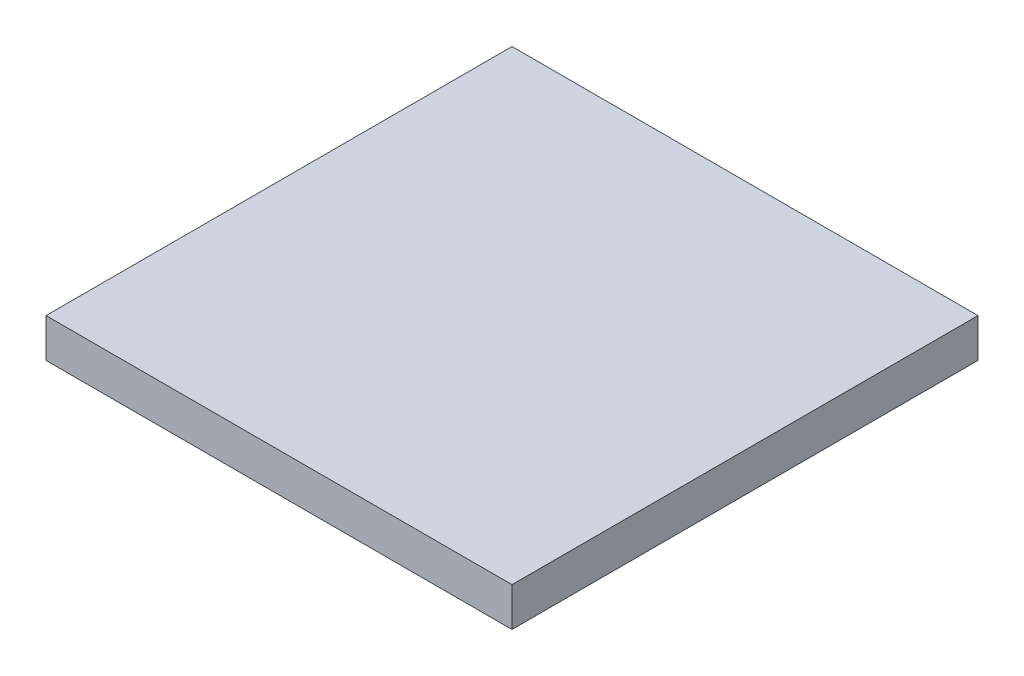
SolidWorks part; units mm, degrees
material "1100-H16 Rod (SS)"
ref_plane "Front Plane" through (0, 0, 0) normal (0, 0, 1) x (1, 0, 0)
ref_plane "Top Plane" through (0, 0, 0) normal (0, 1, 0) x (1, 0, 0)
ref_plane "Right Plane" through (0, 0, 0) normal (1, 0, 0) x (0, 0, -1)
sketch "Sketch1" plane through (0, 0, 0) normal (0, 1, 0) x (1, 0, 0)
  line L1 (-19.05, -19.05) -> (19.05, -19.05)
  line L2 (-19.05, -19.05) -> (-19.05, 19.05)
  line L3 (-19.05, 19.05) -> (19.05, 19.05)
  line L4 (19.05, -19.05) -> (19.05, 19.05)
  line L5 (-19.05, -19.05) -> (19.05, 19.05) construction
  line L6 (-19.05, 19.05) -> (19.05, -19.05) construction
  point P0 (0, 0)
  dimension "D1" = 38.1
  dimension "D2" = 38.1
extrude "Boss-Extrude1" add sketch "Sketch1" along normal blind 3.175
